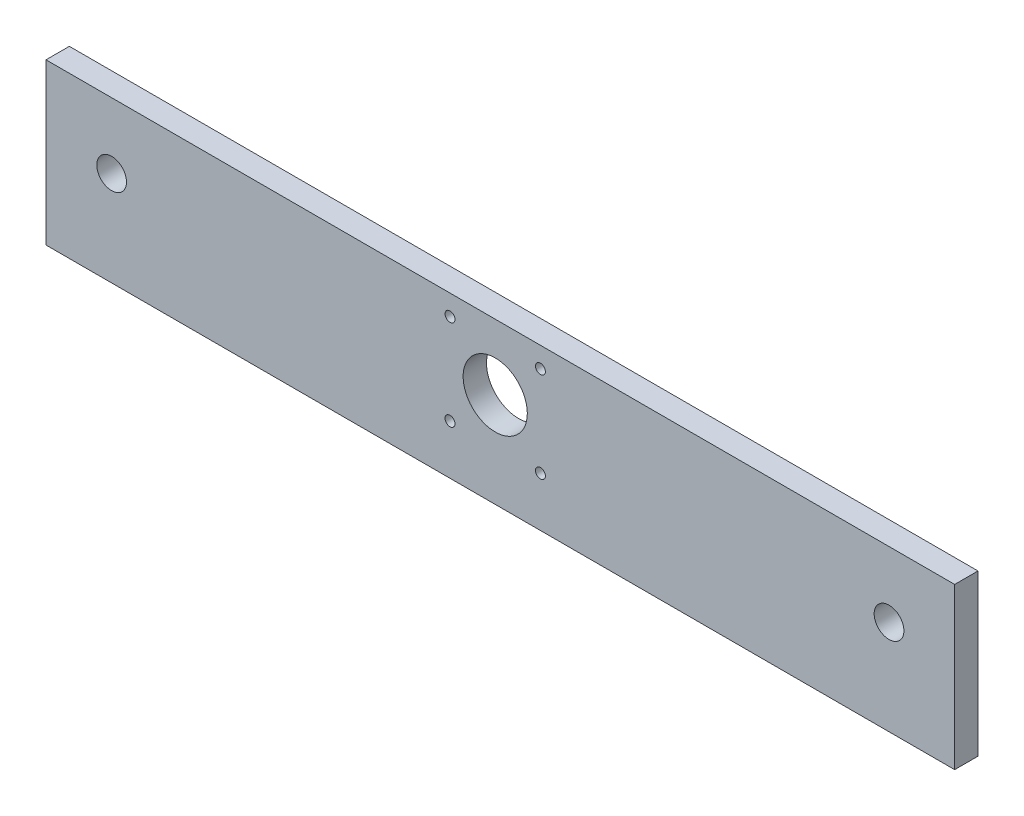
SolidWorks part; units mm, degrees
material "AISI 1020"
ref_plane "Ön Düzlem" through (0, 0, 0) normal (0, 0, 1) x (1, 0, 0)
ref_plane "Üst Düzlem" through (0, 0, 0) normal (0, 1, 0) x (1, 0, 0)
ref_plane "Sağ Düzlem" through (0, 0, 0) normal (1, 0, 0) x (0, 0, -1)
sketch "Sketch1" plane through (0, 0, 0) normal (0, 0, 1) x (1, 0, 0)
  line L1 (155.75, -22.5) -> (-155.75, -22.5)
  line L2 (155.75, -22.5) -> (155.75, 22.5)
  line L3 (155.75, 22.5) -> (-155.75, 22.5)
  line L4 (-155.75, -22.5) -> (-155.75, 22.5)
  line L5 (155.75, -22.5) -> (-155.75, 22.5) construction
  line L6 (155.75, 22.5) -> (-155.75, -22.5) construction
  line L7 (-155.75, 22.5) -> (155.75, 22.5)
  point P0 (0, 0)
  dimension "D1" = 45
  dimension "D2" = 311.5
extrude "Boss-Extrude1" add sketch "Sketch1" along normal mid plane 8 contours L4 L1 L2 L3
hole_wizard "Ø4.6 (4.6) Diameter Hole1" [suppressed] positions "Sketch2" profile "Sketch3" hole size "Ø4.6" standard "ISO"
sketch "Sketch2" plane through (0, 0, 4) normal (0, 0, 1) x (1, 0, 0)
  line L0 (153.25, -22.5) -> (153.25, 22.5) construction
  point P0 (-143.25, 10)
  point P3 (-143.25, -10)
  point P6 (-123.25, -10)
  point P9 (-123.25, 10)
  point P12 (123.25, 10)
  point P15 (143.25, 10)
  point P18 (143.25, -10)
  point P21 (123.25, -10)
  dimension "D1" = 10
  dimension "D2" = 20
  dimension "D3" = 20
  dimension "D4" = 123.25
sketch "Sketch3" plane through (-143.25, 10, 4) normal (1, 0, 0) x (0, -1, 0)
  line L0 (0, 0) -> (0, 8)
  line L1 (0, 8) -> (2.3, 8)
  line L2 (2.3, 8) -> (2.3, 0)
  line L5 (2.3, 0) -> (0, 0)
  line L11 (0, -6.35) -> (0, 107.95) construction
  dimension "Thru Hole Dia." = 4.6
  dimension "Thru Hole Depth" = 8
sketch "Sketch5" plane through (0, 0, 4) normal (0, 0, 1) x (1, 0, 0)
  line L0 (-1.75, -133.5502) -> (-1.75, 93.5502) construction
  line L3 (13.75, -15.5) -> (-17.25, -15.5) construction
  line L4 (13.75, -15.5) -> (13.75, 15.5) construction
  line L5 (13.75, 15.5) -> (-17.25, 15.5) construction
  line L6 (-17.25, -15.5) -> (-17.25, 15.5) construction
  line L7 (13.75, -15.5) -> (-17.25, 15.5) construction
  line L8 (13.75, 15.5) -> (-17.25, -15.5) construction
  circle A0 centre (-1.75, 0) radius 11
  circle A1 centre (-17.25, 15.5) radius 1.25
  circle A2 centre (13.75, 15.5) radius 1.25
  circle A3 centre (13.75, -15.5) radius 1.25
  circle A4 centre (-17.25, -15.5) radius 1.25
  dimension "D1" = 22
  dimension "D2" = 2.5
  dimension "D3" = 2.5
  dimension "D4" = 2.5
  dimension "D5" = 2.5
  dimension "D6" = 31
  dimension "D7" = 31
extrude "Cut-Extrude1" cut sketch "Sketch5" against normal through all
hole_wizard "CBORE for M3 Hex Socket Head Cap Screw1" positions "Sketch8" profile "Sketch9" counterbore size "M3" standard "ISO" end condition through all
sketch "Sketch8" plane through (0, 0, -4) normal (0, 0, -1) x (-1, 0, 0)
  point P0 (-13.75, 15.5)
  point P3 (17.25, 15.5)
  point P6 (17.25, -15.5)
  point P9 (-13.75, -15.5)
sketch "Sketch9" plane through (13.75, 15.5, -4) normal (1, 0, 0) x (0, 1, 0)
  line L0 (0, 0) -> (0, 8)
  line L1 (0, 8) -> (1.7, 8)
  line L3 (1.7, 8) -> (1.7, 3.4)
  line L4 (1.7, 3.4) -> (3.25, 3.4)
  line L5 (3.25, 3.4) -> (3.25, 0)
  line L7 (3.25, 0) -> (0, 0)
  line L11 (0, -6.35) -> (0, 107.95) construction
  dimension "Thru Hole Dia." = 3.4
  dimension "Thru Hole Depth" = 8
  dimension "C'Bore Dia." = 6.5
  dimension "C'Bore Depth" = 3.4
hole_wizard "Ø10.2 (10.2) Diameter Hole1" positions "Sketch12" profile "Sketch13" hole size "Ø10.2" standard "ISO" end condition through all
sketch "Sketch12" plane through (0, 0, 4) normal (0, 0, 1) x (1, 0, 0)
  point P0 (-133.25, 0)
  point P2 (133.25, 0)
  point P17 (0, 0)
  point P18 (0, 0)
  point P19 (0, 0)
sketch "Sketch13" plane through (-133.25, 0, 4) normal (1, 0, 0) x (0, -1, 0)
  line L0 (0, 0) -> (0, 8)
  line L1 (0, 8) -> (5.1, 8)
  line L2 (5.1, 8) -> (5.1, 0)
  line L5 (5.1, 0) -> (0, 0)
  line L11 (0, -6.35) -> (0, 107.95) construction
  dimension "Thru Hole Dia." = 10.2
  dimension "Thru Hole Depth" = 8
fillet "Fillet1" [suppressed] radius 2.5
sketch "Sketch14" plane through (0, 0, 4) normal (0, 0, 1) x (1, 0, 0)
  line L5 (155.75, -22.5) -> (155.75, 22.5) construction
  line L6 (-155.75, -22.5) -> (155.75, -22.5)
  line L7 (-155.75, -22.5) -> (-155.75, -32.5)
  line L8 (-155.75, -32.5) -> (155.75, -32.5)
  line L9 (155.75, -22.5) -> (155.75, -32.5)
  dimension "D1" = 10
extrude "Boss-Extrude2" add sketch "Sketch14" against normal blind 8
